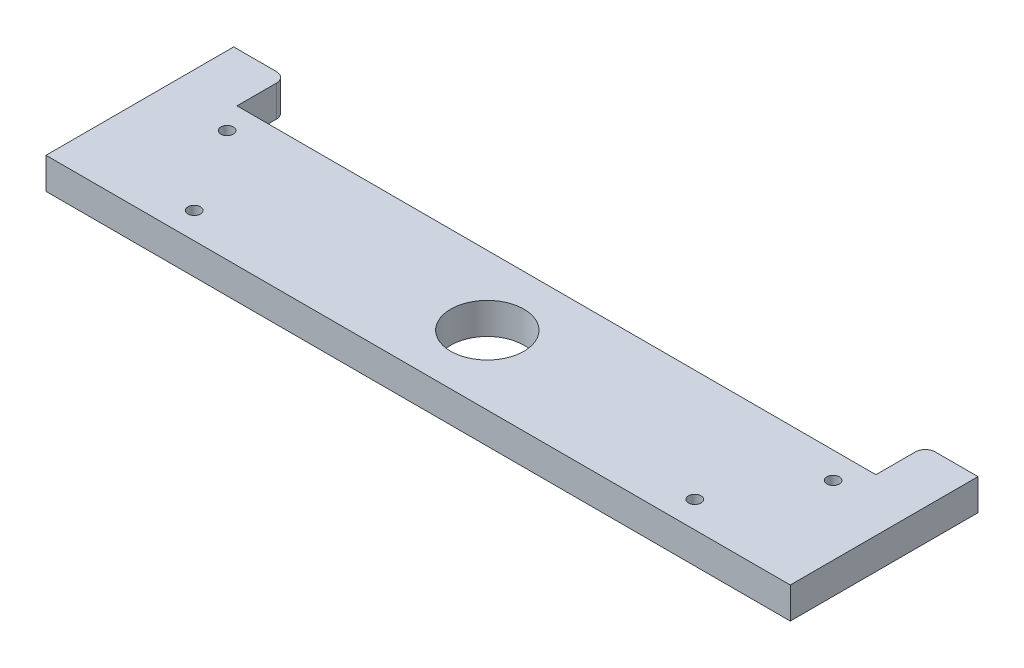
SolidWorks part; units mm, degrees
ref_plane "前视基准面" through (0, 0, 0) normal (0, 0, 1) x (1, 0, 0)
ref_plane "上视基准面" through (0, 0, 0) normal (0, 1, 0) x (1, 0, 0)
ref_plane "右视基准面" through (0, 0, 0) normal (1, 0, 0) x (0, 0, -1)
sketch "草图1" plane through (0, 0, 0) normal (0, 1, 0) x (1, 0, 0)
  line L1 (0, 42) -> (226, 42)
  line L2 (0, 42) -> (0, 0)
  line L3 (0, 0) -> (226, 0)
  line L4 (226, 42) -> (226, 0)
  dimension "D1" = 226
  dimension "D2" = 42
extrude "凸台-拉伸1" add sketch "草图1" along normal blind 9.5
sketch "草图6" plane through (0, 0, -42) normal (0, 0, -1) x (-1, 0, 0)
  line L0 (-226, 9.5) -> (0, 9.5) construction
  line L1 (0, 0) -> (-16, 0)
  line L2 (0, 0) -> (0, 9.5)
  line L3 (0, 9.5) -> (-16, 9.5)
  line L4 (-16, 0) -> (-16, 9.5)
  line L5 (-226, 0) -> (0, 0) construction
  line L6 (-226, 9.5) -> (-210, 9.5)
  line L7 (-226, 9.5) -> (-226, 0)
  line L8 (-226, 0) -> (-210, 0)
  line L9 (-210, 9.5) -> (-210, 0)
  dimension "D1" = 16
  dimension "D2" = 16
extrude "凸台-拉伸4" add sketch "草图6" along normal blind 15
fillet "圆角1" radius 3 2 edges at (210, 4.75, -57) (16, 4.75, -57)
sketch "草图7" plane through (0, 9.5, 0) normal (0, 1, 0) x (1, 0, 0)
  circle A4 centre (21, 34) radius 1.9
  circle A6 centre (37, 8) radius 1.9
  circle A8 centre (189, 8) radius 1.9
  circle A9 centre (205, 34) radius 1.9
  dimension "D2" = 3.8
extrude "切除-拉伸1" cut sketch "草图7" against normal through all
sketch "草图9" plane through (0, 9.5, 0) normal (0, 1, 0) x (1, 0, 0)
  circle A0 centre (113, 21) radius 11.1
  dimension "D1" = 22.2
extrude "切除-拉伸2" cut sketch "草图9" against normal blind 10
sketch "草图11" plane through (0, 0, 0) normal (0, -1, 0) x (1, 0, 0)
  circle A0 centre (37, -8) radius 4
  circle A1 centre (21, -34) radius 4
  circle A2 centre (189, -8) radius 4
  circle A3 centre (205, -34) radius 4
  dimension "D1" = 8
extrude "切除-拉伸4" cut sketch "草图11" against normal blind 4
